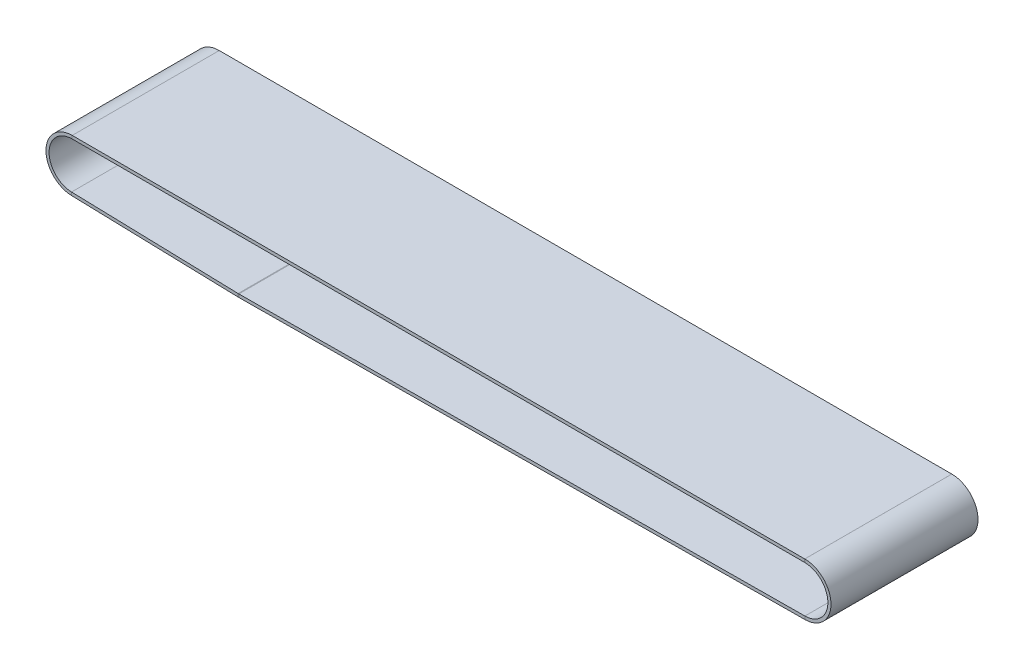
SolidWorks part; units mm, degrees
ref_plane "Front Plane" through (0, 0, 0) normal (0, 0, 1) x (1, 0, 0)
ref_plane "Top Plane" through (0, 0, 0) normal (0, 1, 0) x (1, 0, 0)
ref_plane "Right Plane" through (0, 0, 0) normal (1, 0, 0) x (0, 0, -1)
sketch "Sketch2" plane through (0, 0, 0) normal (0, 0, 1) x (1, 0, 0)
  line L0 (0, 0) -> (1, 0) construction
  line L1 (0, 0) -> (0, 1) construction
  line L2 (0.1635, -22.4994) -> (-550.3786, -26.4995)
  line L3 (-551.0794, -26.4923) -> (-713.0829, -21.9913)
  line L4 (-712.4422, 23) -> (0.0158, 22.5)
  arc A0 (0.0158, 22.5) -> (0.1635, -22.4994) centre (0, 0) cw
  arc A1 (-550.3786, -26.4995) -> (-551.0794, -26.4923) centre (-550.5239, -6.5) cw
  arc A2 (-713.0829, -21.9913) -> (-712.4422, 23) centre (-712.458, 0.5) cw
sketch "Sketch3" plane through (0, 0, 0) normal (1, 0, 0) x (0, 0, -1)
  line L0 (-71.5, 22.5) -> (71.5, 22.5)
  line L1 (71.5, 22.5) -> (71.5, 25.5)
  line L2 (71.5, 25.5) -> (-71.5, 25.5)
  line L3 (-71.5, 25.5) -> (-71.5, 22.5)
  point P2 (0, 22.5)
  dimension "D1" = 143
  dimension "D2" = 3
sweep "Sweep1" add profiles "Sketch3" path "Sketch2"
